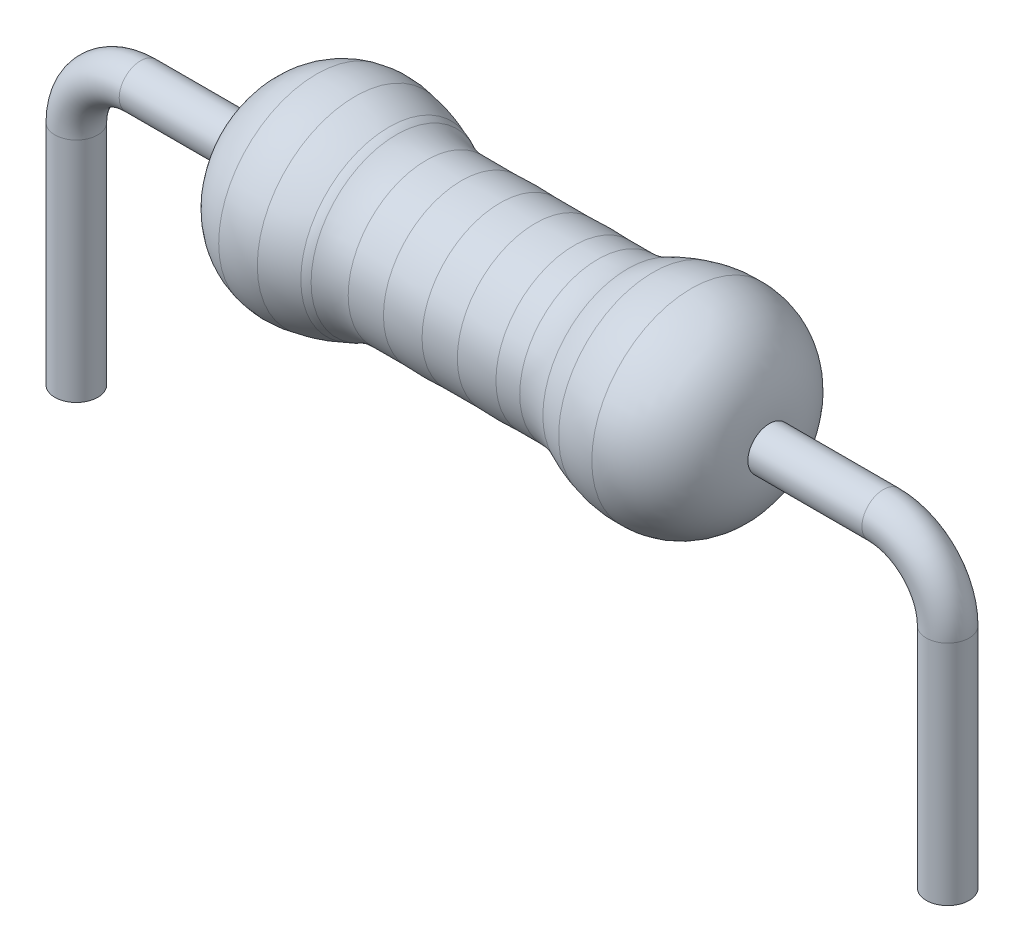
SolidWorks part; units mm, degrees
material "Plain Carbon Steel"
ref_plane "Front Plane" through (0, 0, 0) normal (0, 0, 1) x (1, 0, 0)
ref_plane "Top Plane" through (0, 0, 0) normal (0, 1, 0) x (1, 0, 0)
ref_plane "Right Plane" through (0, 0, 0) normal (1, 0, 0) x (0, 0, -1)
sketch "Sketch1" plane through (0, 0, 0) normal (0, 0, 1) x (1, 0, 0)
  line L0 (-4.33, 0) -> (4.33, 0)
  line L1 (-5.08, -0.75) -> (-5.08, -3.4)
  line L2 (5.08, -0.75) -> (5.08, -3.4)
  line L3 (-5.08, -3.4) -> (5.08, -3.4) construction
  line L4 (0, 0) -> (0, -3.4) construction
  arc A0 (-4.33, 0) -> (-5.08, -0.75) centre (-4.33, -0.75) ccw
  arc A1 (4.33, 0) -> (5.08, -0.75) centre (4.33, -0.75) cw
  dimension "D2" = 0.75
  dimension "D1" = 10.16
  dimension "D3" = 3.4
ref_plane "Plane1" through (-5.08, -3.4, 0) normal (0, -1, 0) x (-1, 0, 0)
sketch "Sketch2" plane through (-5.08, -3.4, 0) normal (0, -1, 0) x (-1, 0, 0)
  circle A0 centre (0, 0) radius 0.25
  dimension "D1" = 0.5
sweep "Sweep1" add profiles "Sketch2" path "Sketch1"
sketch "Sketch3" plane through (0, 0, 0) normal (0, 0, 1) x (1, 0, 0)
  line L0 (-3, 0) -> (3, 0)
  line L5 (-3, 0) -> (-3, 1.16)
  line L6 (3, 0) -> (3, 1.16)
  line L7 (-3, 1.16) -> (-1, 1.16)
  line L8 (3, 1.16) -> (1, 1.16)
  line L9 (-1, 1.16) -> (-1, 0.91)
  line L10 (-1, 0.91) -> (1, 0.91)
  line L11 (1, 0.91) -> (1, 1.16)
  line L12 (0, 0) -> (0, 0.91) construction
  line L13 (4.33, 0.25) -> (-4.33, 0.25) construction
  line L14 (-1.35, 0.9903) -> (-1, 0.9903) construction
  line L16 (1, 0.9903) -> (1.35, 0.9903) construction
  arc A0 (-3, 0.25) -> (-2.09, 1.16) centre (-2.09, 0.25) cw
  arc A1 (-2.09, 1.16) -> (-1.35, 0.9903) centre (-2.09, -0.5381) cw
  arc A2 (-1.35, 0.9903) -> (-1, 0.91) centre (-1, 1.7131) ccw
  arc A3 (1, 0.91) -> (1.35, 0.9903) centre (1, 1.7131) ccw
  arc A4 (1.35, 0.9903) -> (2.09, 1.16) centre (2.09, -0.5381) cw
  arc A5 (2.09, 1.16) -> (3, 0.25) centre (2.09, 0.25) cw
  dimension "D1" = 6
  dimension "D2" = 1.16
  dimension "D3" = 2
  dimension "D4" = 0.91
  dimension "D5" = 0.35
revolve "Revolve1" add sketch "Sketch3" angle 360 about L0
sketch "Sketch5" plane through (0, 0, 0) normal (0, 0, 1) x (1, 0, 0)
  line L0 (-1, 0.91) -> (1, 0.91)
  line L1 (-0.5888, 0.91) -> (-0.1388, 0.91)
  line L2 (0.2724, 0.91) -> (0.7224, 0.91)
  line L3 (1.644, 1.1004) -> (2.09, 1.16)
  line L4 (-1.4342, 1.0282) -> (-1, 0.91)
  line L5 (-2.2799, 1.14) -> (-1.8299, 1.14)
  line L6 (-1, 0.91) -> (1, 0.91) construction
  line L7 (-1, 0.91) -> (-0.5888, 0.91)
  line L8 (-1.4342, 1.0282) -> (-1.8299, 1.14)
  line L9 (-0.1388, 0.91) -> (0.2724, 0.91)
  line L10 (-1.35, 0.9903) -> (-1.3479, 0.9946) construction
  line L12 (-1.3457, 0.9882) -> (-1.35, 0.9903) construction
  arc A0 (-2.09, 1.16) -> (-3, 0.25) centre (-2.09, 0.25) ccw
  arc A1 (-2.09, 1.16) -> (-1.35, 0.9903) centre (-2.09, -0.5381) cw
  arc A2 (-1.35, 0.9903) -> (-1, 0.91) centre (-1, 1.7131) ccw
  arc A3 (1, 0.91) -> (1.35, 0.9903) centre (1, 1.7131) ccw
  arc A4 (1.35, 0.9903) -> (2.09, 1.16) centre (2.09, -0.5381) cw
  arc A5 (2.09, 1.16) -> (3, 0.25) centre (2.09, 0.25) cw
  arc A6 (-2.09, 1.16) -> (-3, 0.25) centre (-2.09, 0.25) ccw construction
  arc A7 (-1.35, 0.9903) -> (-2.09, 1.16) centre (-2.09, -0.5381) ccw construction
  arc A8 (-1.35, 0.9903) -> (-1, 0.91) centre (-1, 1.7131) ccw construction
  arc A9 (1, 0.91) -> (1.35, 0.9903) centre (1, 1.7131) ccw construction
  arc A10 (2.09, 1.16) -> (1.35, 0.9903) centre (2.09, -0.5381) ccw construction
  arc A11 (3, 0.25) -> (2.09, 1.16) centre (2.09, 0.25) ccw construction
  arc A12 (-0.5888, 0.91) -> (-0.1388, 0.91) centre (-0.3638, -4.0849) cw
  arc A13 (0.2724, 0.91) -> (0.7224, 0.91) centre (0.4974, -4.0849) cw
  arc A14 (1.644, 1.1004) -> (2.09, 1.16) centre (2.0501, -0.2394) cw
  arc A16 (-2.2799, 1.14) -> (-1.8299, 1.14) centre (-2.0549, 0.1656) cw
  arc A17 (-1.4342, 1.0282) -> (-1.3479, 0.9946) centre (-1.5496, 0.6046) cw
  arc A18 (-1.3479, 0.9946) -> (-1, 0.91) centre (-1, 1.6674) ccw
  dimension "D2" = 5
  dimension "D3" = 1
  dimension "D4" = 1.4
  dimension "D1" = 0.45
revolve "Revolve2" add sketch "Sketch5" angle 360 about L0
